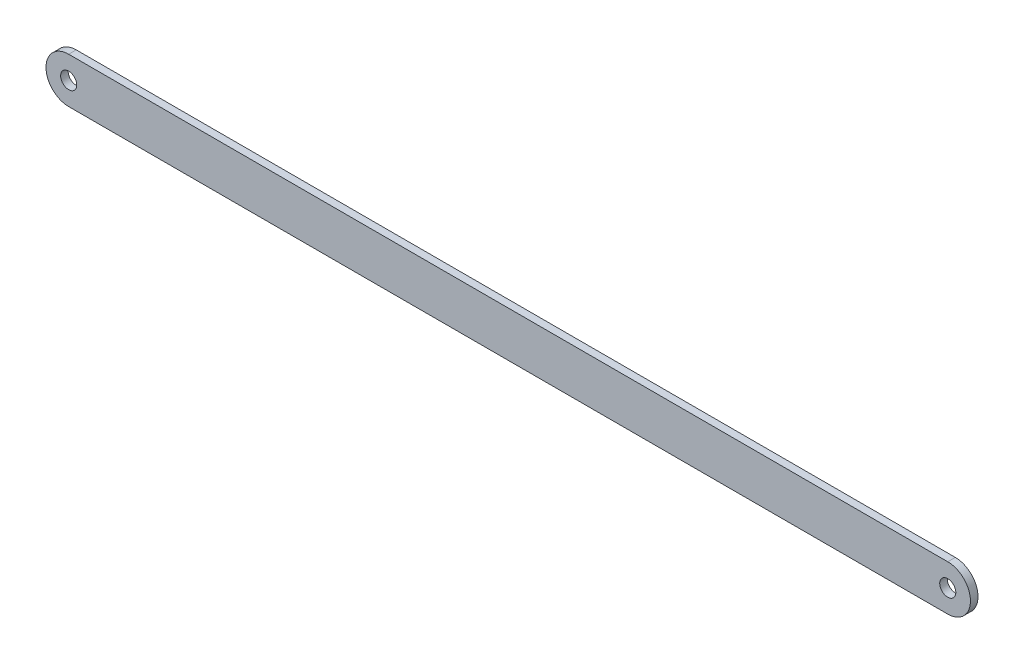
SolidWorks part; units mm, degrees
material "6063-O"
ref_plane "Front Plane" through (0, 0, 0) normal (0, 0, 1) x (1, 0, 0)
ref_plane "Top Plane" through (0, 0, 0) normal (0, 1, 0) x (1, 0, 0)
ref_plane "Right Plane" through (0, 0, 0) normal (1, 0, 0) x (0, 0, -1)
sketch "Sketch2" plane through (0, 0, 0) normal (0, 0, 1) x (1, 0, 0)
  line L0 (184.5874, 0) -> (-184.5874, 0) construction
  line L1 (1.7463, 0) -> (-1.7463, 0) construction
  line L2 (184.5874, -9.525) -> (-184.5874, -9.525)
  line L3 (184.5874, 9.525) -> (-184.5874, 9.525)
  line L4 (-184.5874, 0) -> (-26.8689, -182.6214) construction
  line L5 (-26.8689, -182.6214) -> (184.5874, 0) construction
  arc A0 (184.5874, -9.525) -> (184.5874, 9.525) centre (184.5874, 0) ccw
  arc A1 (-184.5874, 9.525) -> (-184.5874, -9.525) centre (-184.5874, 0) ccw
  point P5 (0, 0)
  dimension "D1" = 19.05
  dimension "D2" = 388.2248
  dimension "D3" = 241.3
  dimension "D4" = 279.4
extrude "Boss-Extrude1" add sketch "Sketch2" along normal mid plane 3.175
hole_wizard "1/4 Clearance Hole1" positions "Sketch4" profile "Sketch5" hole size "1/4" standard "ANSI Inch" end condition through all
sketch "Sketch4" plane through (0, 0, 1.5875) normal (0, 0, 1) x (1, 0, 0)
  point P0 (-184.5874, 0)
  point P3 (184.5874, 0)
sketch "Sketch5" plane through (-184.5874, 0, 1.5875) normal (1, 0, 0) x (0, -1, 0)
  line L0 (0, 0) -> (0, 3.175)
  line L1 (0, 3.175) -> (3.3782, 3.175)
  line L2 (3.3782, 3.175) -> (3.3782, 0)
  line L5 (3.3782, 0) -> (0, 0)
  line L11 (0, -6.35) -> (0, 107.95) construction
  dimension "Thru Hole Dia." = 6.7564
  dimension "Thru Hole Depth" = 3.175
